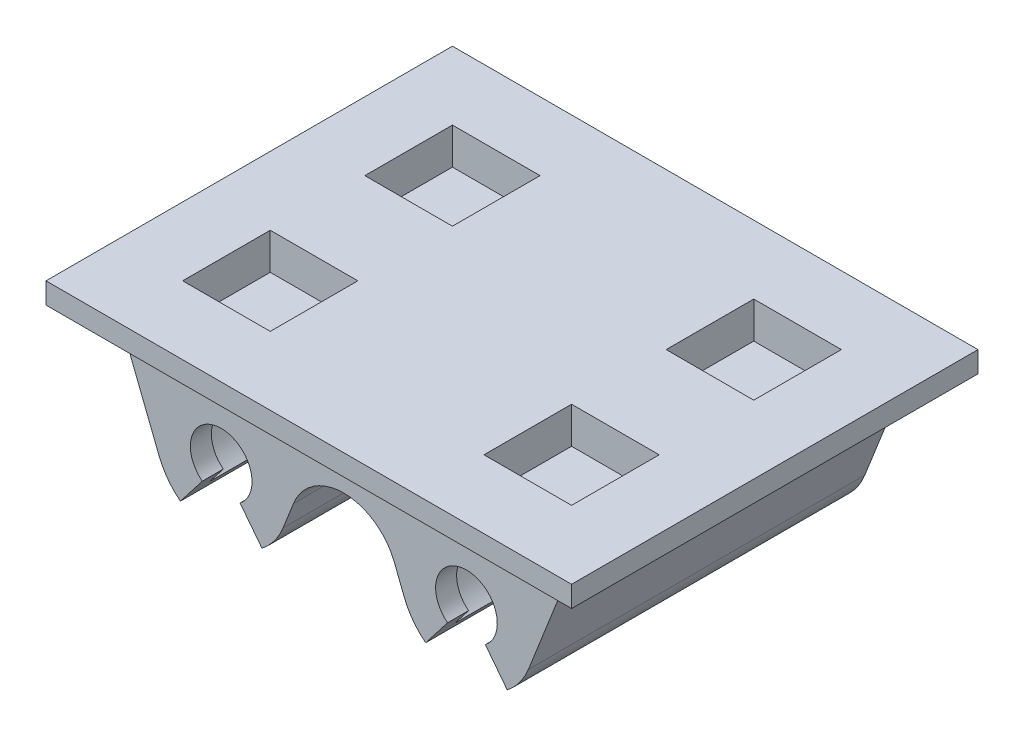
SolidWorks part; units mm, degrees
ref_plane "Front Plane" through (0, 0, 0) normal (0, 0, 1) x (1, 0, 0)
ref_plane "Top Plane" through (0, 0, 0) normal (0, 1, 0) x (1, 0, 0)
ref_plane "Right Plane" through (0, 0, 0) normal (1, 0, 0) x (0, 0, -1)
sketch "Sketch1" plane through (0, 0, 0) normal (0, 0, 1) x (1, 0, 0)
  line L0 (-32.6359, 12.1293) -> (32.3641, 12.1293)
  line L1 (32.3641, 12.1293) -> (26.2008, -3.4875)
  line L2 (-32.6359, 12.1293) -> (-26.4727, -3.4875)
  line L3 (-17.6359, 0) -> (-17.6359, 16.0147) construction
  line L4 (-0.1359, 12.1293) -> (-0.1359, -10.2913) construction
  line L5 (-23.4525, -7.5112) -> (-22.2892, -6.009)
  line L6 (-11.8194, -7.5112) -> (-12.9827, -6.009)
  line L7 (-7.3183, 0.2648) -> (-8.7992, -3.4875)
  line L8 (23.1806, -7.5112) -> (22.0173, -6.009)
  line L9 (11.5475, -7.5112) -> (12.7108, -6.009)
  line L10 (7.0464, 0.2648) -> (8.5273, -3.4875)
  arc A0 (-12.9827, -6.009) -> (-22.2892, -6.009) centre (-17.6359, 0) ccw
  arc A1 (22.0173, -6.009) -> (12.7108, -6.009) centre (17.3641, 0) ccw
  arc A2 (-11.8194, -7.5112) -> (-8.7992, -3.4875) centre (-17.6359, 0) ccw
  arc A3 (23.1806, -7.5112) -> (26.2008, -3.4875) centre (17.3641, 0) ccw
  arc A4 (7.0464, 0.2648) -> (-7.3183, 0.2648) centre (-0.1359, -2.5697) ccw
  circle A5 centre (-17.6359, 0) radius 9.5 construction
  circle A6 centre (-17.6359, 0) radius 7.6 construction
  circle A7 centre (17.3641, 0) radius 9.5 construction
  circle A8 centre (17.3641, 0) radius 7.6 construction
  arc A9 (-26.4727, -3.4875) -> (-23.4525, -7.5112) centre (-17.6359, 0) ccw
  arc A10 (8.5273, -3.4875) -> (11.5475, -7.5112) centre (17.3641, 0) ccw
  dimension "D1" = 35
  dimension "D4" = 65
  dimension "D5" = 15
extrude "Boss-Extrude1" add sketch "Sketch1" along normal blind 48
sketch "Sketch2" plane through (0, 0, 48) normal (0, 0, 1) x (1, 0, 0)
  line L0 (22.0173, -6.009) -> (20.058, -3.4789)
  line L1 (12.7108, -6.009) -> (14.6701, -3.4789)
  line L2 (-12.9827, -6.009) -> (-14.942, -3.4789)
  line L3 (-22.2892, -6.009) -> (-20.3299, -3.4789)
  arc A0 (22.0173, -6.009) -> (12.7108, -6.009) centre (17.3641, 0) ccw
  arc A1 (20.058, -3.4789) -> (14.6701, -3.4789) centre (17.3641, 0) ccw
  arc A2 (-12.9827, -6.009) -> (-22.2892, -6.009) centre (-17.6359, 0) ccw
  arc A3 (-14.942, -3.4789) -> (-20.3299, -3.4789) centre (-17.6359, 0) ccw
extrude "Boss-Extrude2" add sketch "Sketch2" against normal blind 3
sketch "Sketch3" plane through (0, 12.1293, 0) normal (0, 1, 0) x (1, 0, 0)
  line L0 (32.3641, -48) -> (32.3641, 0) construction
  line L1 (37.3641, 5) -> (-37.6359, 5)
  line L2 (37.3641, 5) -> (37.3641, -53)
  line L3 (37.3641, -53) -> (-37.6359, -53)
  line L4 (-37.6359, 5) -> (-37.6359, -53)
  line L5 (32.3641, 0) -> (-32.6359, 0) construction
  dimension "D1" = 75
  dimension "D2" = 58
  dimension "D3" = 5
  dimension "D4" = 5
extrude "Boss-Extrude3" add sketch "Sketch3" along normal blind 3
sketch "Sketch4" plane through (0, 15.1293, 0) normal (0, 1, 0) x (1, 0, 0)
  line L0 (37.3641, -24) -> (-37.6359, -24) construction
  line L1 (27.6141, -4.75) -> (15.1141, -4.75)
  line L2 (27.6141, -4.75) -> (27.6141, -17.25)
  line L3 (27.6141, -17.25) -> (15.1141, -17.25)
  line L4 (15.1141, -4.75) -> (15.1141, -17.25)
  line L5 (37.3641, -53) -> (37.3641, 5) construction
  line L6 (-37.6359, 5) -> (-37.6359, -53) construction
  line L7 (-0.1359, 5) -> (-0.1359, -53) construction
  line L8 (37.3641, 5) -> (-37.6359, 5) construction
  line L9 (-37.6359, -53) -> (37.3641, -53) construction
  line L10 (15.1141, -43.25) -> (15.1141, -30.75)
  line L11 (27.6141, -30.75) -> (15.1141, -30.75)
  line L12 (27.6141, -43.25) -> (27.6141, -30.75)
  line L13 (27.6141, -43.25) -> (15.1141, -43.25)
  line L14 (-27.8859, -43.25) -> (-15.3859, -43.25)
  line L15 (-27.8859, -43.25) -> (-27.8859, -30.75)
  line L16 (-27.8859, -30.75) -> (-15.3859, -30.75)
  line L17 (-15.3859, -43.25) -> (-15.3859, -30.75)
  line L18 (-15.3859, -4.75) -> (-15.3859, -17.25)
  line L19 (-27.8859, -17.25) -> (-15.3859, -17.25)
  line L20 (-27.8859, -4.75) -> (-27.8859, -17.25)
  line L21 (-27.8859, -4.75) -> (-15.3859, -4.75)
  dimension "D1" = 12.5
  dimension "D2" = 12.5
  dimension "D3" = 9.75
  dimension "D4" = 9.75
extrude "Cut-Extrude1" cut sketch "Sketch4" against normal blind 5.2
